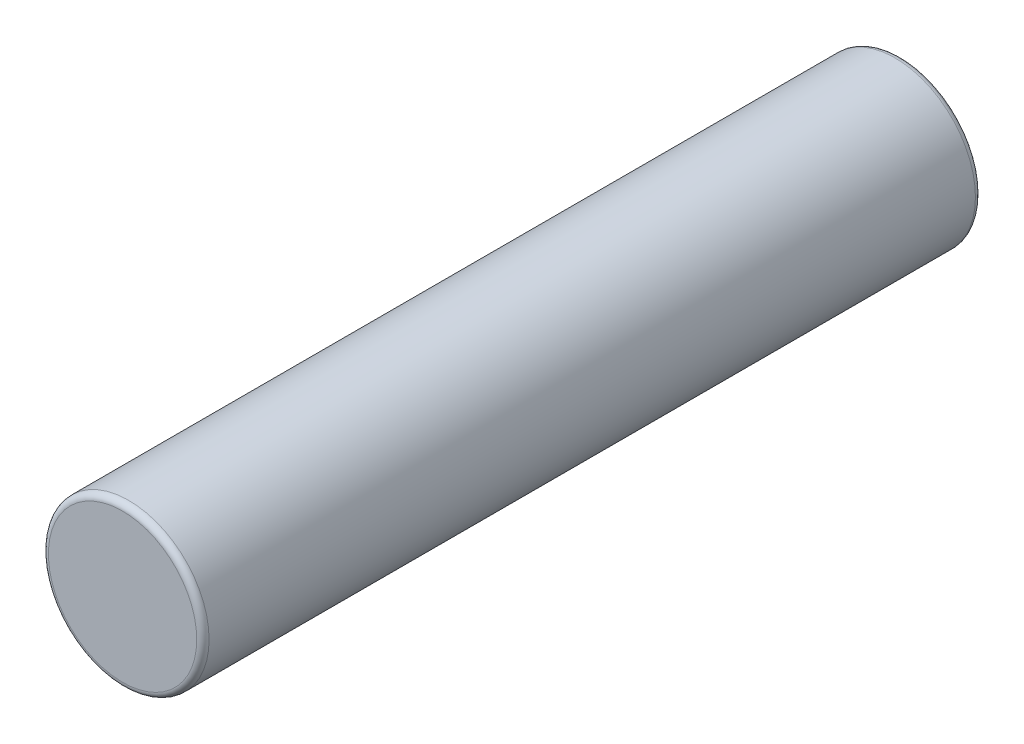
SolidWorks part; units mm, degrees
ref_plane "Front Plane" through (0, 0, 0) normal (0, 0, 1) x (1, 0, 0)
ref_plane "Top Plane" through (0, 0, 0) normal (0, 1, 0) x (1, 0, 0)
ref_plane "Right Plane" through (0, 0, 0) normal (1, 0, 0) x (0, 0, -1)
sketch "Sketch1" plane through (0, 0, 0) normal (0, 0, 1) x (1, 0, 0)
  circle A0 centre (0, 0) radius 6.5
  dimension "D1" = 13
extrude "Boss-Extrude1" add sketch "Sketch1" along normal blind 63
fillet "Fillet1" radius 0.5 2 edges at (6.5, 0, 0) (6.5, 0, 63)
